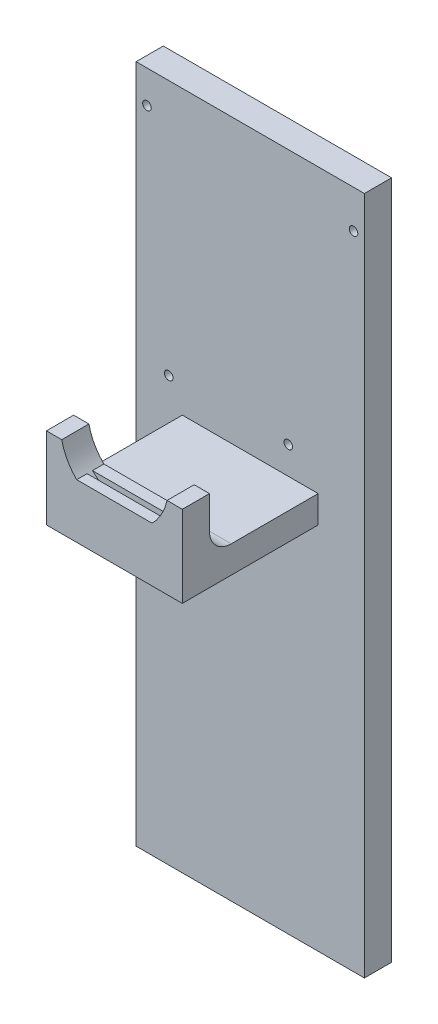
SolidWorks part; units mm, degrees
ref_plane "Front Plane" through (0, 0, 0) normal (0, 0, 1) x (1, 0, 0)
ref_plane "Top Plane" through (0, 0, 0) normal (0, 1, 0) x (1, 0, 0)
ref_plane "Right Plane" through (0, 0, 0) normal (1, 0, 0) x (0, 0, -1)
sketch "Sketch1" plane through (0, 0, 0) normal (0, 0, 1) x (1, 0, 0)
  line L0 (-43.7614, 78.5105) -> (9.5786, 78.5105) construction
  line L1 (-43.7614, 129.3105) -> (9.5786, 129.3105)
  line L2 (-43.7614, 129.3105) -> (-43.7614, -29.4395)
  line L3 (-43.7614, -29.4395) -> (9.5786, -29.4395)
  line L4 (9.5786, 129.3105) -> (9.5786, -29.4395)
  line L5 (-43.7614, 69.6205) -> (9.5786, 69.6205) construction
  line L6 (-43.7614, 121.6905) -> (9.5786, 121.6905) construction
  line L7 (-43.7614, 120.4205) -> (9.5786, 120.4205) construction
  circle A0 centre (-36.1414, 69.6205) radius 1
  circle A1 centre (-8.2014, 69.6205) radius 1
  circle A2 centre (-41.2214, 121.6905) radius 1
  circle A4 centre (7.0386, 120.4205) radius 1
  dimension "D5" = 2
  dimension "D7" = 2
  dimension "D8" = 27.94
  dimension "D10" = 2
  dimension "D11" = 1.27
  dimension "D13" = 2
  dimension "D1" = 158.75
  dimension "D2" = 53.34
  dimension "D3" = 107.95
  dimension "D4" = 8.89
  dimension "D6" = 7.62
  dimension "D9" = 52.07
  dimension "D12" = 2.54
  dimension "D14" = 48.26
extrude "Boss-Extrude1" add sketch "Sketch1" along normal blind 6.35
sketch "Sketch2" plane through (0, 0, 6.35) normal (0, 0, 1) x (1, 0, 0)
  line L0 (-43.7614, 78.5105) -> (9.5786, 78.5105) construction
  line L1 (-43.7614, 129.3105) -> (-43.7614, -29.4395) construction
  line L2 (9.5786, -29.4395) -> (9.5786, 129.3105) construction
  line L3 (-43.7614, -29.4395) -> (9.5786, -29.4395) construction
  line L5 (-32.9664, 63.1891) -> (-1.2164, 63.1891)
  line L6 (-32.9664, 63.1891) -> (-32.9664, 56.8391)
  line L7 (-32.9664, 56.8391) -> (-1.2164, 56.8391)
  line L8 (-1.2164, 63.1891) -> (-1.2164, 56.8391)
  circle A0 centre (-17.0914, 78.5105) radius 12.573 construction
  point P14 (-17.0914, 56.8391)
  dimension "D2" = 25.146
  dimension "D1" = 107.95
  dimension "D3" = 31.75
  dimension "D4" = 6.35
  dimension "D5" = 26.67
extrude "Boss-Extrude2" add sketch "Sketch2" along normal blind 31.75
sketch "Sketch3" plane through (0, 63.1891, 0) normal (0, 1, 0) x (1, 0, 0)
  line L0 (-1.2164, -38.1) -> (-1.2164, -6.35) construction
  line L1 (-32.9664, -38.1) -> (-1.2164, -38.1)
  line L2 (-32.9664, -38.1) -> (-32.9664, -31.75)
  line L3 (-32.9664, -31.75) -> (-1.2164, -31.75)
  line L4 (-1.2164, -38.1) -> (-1.2164, -31.75)
  dimension "D1" = 6.35
extrude "Boss-Extrude3" add sketch "Sketch3" along normal blind 12.7
sketch "Sketch4" plane through (0, 0, 38.1) normal (0, 0, 1) x (1, 0, 0)
  line L0 (-43.7614, 78.5105) -> (9.5786, 78.5105) construction
  line L1 (-43.7614, 129.3105) -> (-43.7614, -29.4395) construction
  line L2 (9.5786, -29.4395) -> (9.5786, 129.3105) construction
  line L3 (-43.7614, -29.4395) -> (9.5786, -29.4395) construction
  circle A0 centre (-17.0914, 78.5105) radius 12.573
  dimension "D2" = 25.146
  dimension "D1" = 107.95
extrude "Cut-Extrude1" cut sketch "Sketch4" against normal up to next
sketch "Sketch5" plane through (0, 63.1891, 0) normal (0, 1, 0) x (1, 0, 0)
  line L0 (-1.2164, -38.1) -> (-1.2164, -31.75) construction
  line L1 (-32.9664, -31.75) -> (-1.2164, -31.75)
  line L2 (-32.9664, -31.75) -> (-32.9664, -34.4212)
  line L3 (-32.9664, -34.4212) -> (-1.2164, -34.4212)
  line L4 (-1.2164, -31.75) -> (-1.2164, -34.4212)
  line L5 (-32.9664, -31.75) -> (-32.9664, -38.1) construction
  line L6 (-1.2164, -38.1) -> (-32.9664, -38.1)
  line L7 (-1.2164, -38.1) -> (-1.2164, -35.6712)
  line L8 (-1.2164, -35.6712) -> (-32.9664, -35.6712)
  line L9 (-32.9664, -38.1) -> (-32.9664, -35.6712)
  dimension "D1" = 1.25
  dimension "D2" = 2.6712
extrude "Boss-Extrude4" add sketch "Sketch5" along normal blind 6.35
fillet "Fillet1" radius 5.08 1 edges at (-17.0914, 63.1891, 31.75)
